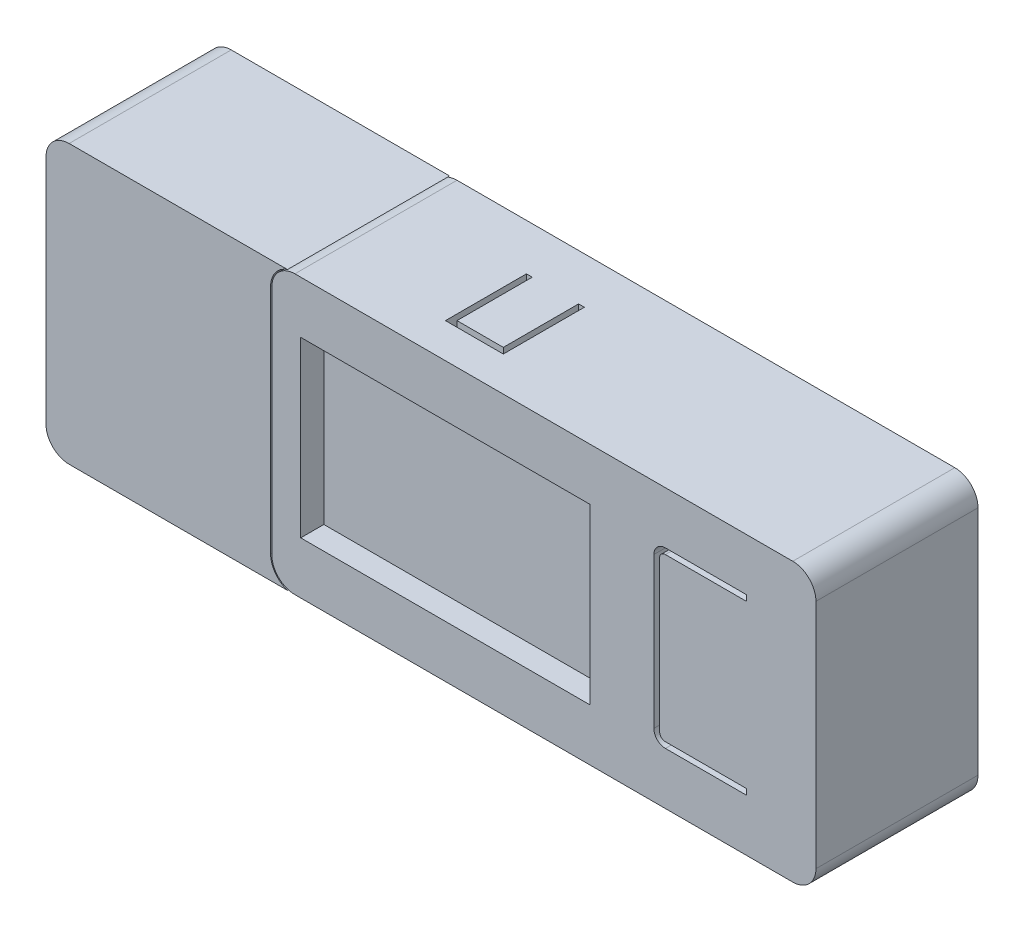
SolidWorks part; units mm, degrees
ref_plane "Alzado" through (0, 0, 0) normal (0, 0, 1) x (1, 0, 0)
ref_plane "Planta" through (0, 0, 0) normal (0, 1, 0) x (1, 0, 0)
ref_plane "Vista lateral" through (0, 0, 0) normal (1, 0, 0) x (0, 0, -1)
sketch "Croquis1" plane through (0, 0, 0) normal (0, 0, 1) x (1, 0, 0)
  line L1 (23.5, 12) -> (-23.5, 12)
  line L2 (23.5, 12) -> (23.5, -12)
  line L3 (23.5, -12) -> (-23.5, -12)
  line L4 (-23.5, 12) -> (-23.5, -12)
  line L5 (23.5, 12) -> (-23.5, -12) construction
  line L6 (23.5, -12) -> (-23.5, 12) construction
  point P0 (0, 0)
  dimension "D1" = 47
  dimension "D2" = 24
extrude "Saliente-Extruir1" add sketch "Croquis1" along normal blind 14
fillet "Redondeo1" radius 2 4 edges at (-23.5, -12, 7) (-23.5, 12, 7) (23.5, -12, 7) (23.5, 12, 7)
sketch "Croquis2" plane through (0, 0, 14) normal (0, 0, 1) x (1, 0, 0)
  line L0 (23.5, -10) -> (23.5, 10) construction
  line L1 (4, 7.5) -> (-21, 7.5)
  line L2 (4, 7.5) -> (4, -7.5)
  line L3 (4, -7.5) -> (-21, -7.5)
  line L4 (-21, 7.5) -> (-21, -7.5)
  line L5 (4, 7.5) -> (-21, -7.5) construction
  line L6 (4, -7.5) -> (-21, 7.5) construction
  line L7 (17.5, 7.5) -> (10.5, 7.5)
  line L8 (9.5, 6.5) -> (9.5, -6.5)
  line L9 (10.5, -7.5) -> (17.5, -7.5)
  line L10 (17.5, 7) -> (10.5, 7)
  line L11 (10, 6.5) -> (10, -6.5)
  line L12 (10.5, -7) -> (17.5, -7)
  line L13 (17.5, 7.5) -> (17.5, 7)
  line L14 (17.5, -7) -> (17.5, -7.5)
  arc A0 (10.5, 7.5) -> (9.5, 6.5) centre (10.5, 6.5) ccw
  arc A1 (9.5, -6.5) -> (10.5, -7.5) centre (10.5, -6.5) ccw
  arc A2 (10.5, 7) -> (10, 6.5) centre (10.5, 6.5) ccw
  arc A3 (10, -6.5) -> (10.5, -7) centre (10.5, -6.5) ccw
  point P0 (-8.5, 0)
  point P5 (9.5, 0)
  dimension "D6" = 1
  dimension "D1" = 25
  dimension "D2" = 19.5
  dimension "D3" = 15
  dimension "D4" = 8
  dimension "D5" = 6
  dimension "D7" = 0.5
extrude "Cortar-Extruir1" cut sketch "Croquis2" against normal blind 2
sketch "Croquis3" plane through (0, 12, 0) normal (0, 1, 0) x (1, 0, 0)
  line L0 (-6.5, -4) -> (-6.5, -11)
  line L1 (-6.5, -11) -> (-11.5, -11)
  line L2 (-11.5, -11) -> (-11.5, -4)
  line L3 (23.5, 0) -> (23.5, -14) construction
  line L4 (21.5, -14) -> (-21.5, -14) construction
  line L5 (21.5, 0) -> (-21.5, 0) construction
  line L6 (-7, -4) -> (-7, -10.5)
  line L7 (-7, -10.5) -> (-11, -10.5)
  line L8 (-11, -10.5) -> (-11, -4)
  line L9 (-11.5, -4) -> (-11, -4)
  line L10 (-7, -4) -> (-6.5, -4)
  dimension "D1" = 30
  dimension "D2" = 5
  dimension "D3" = 3
  dimension "D4" = 4
  dimension "D5" = 0.5
extrude "Cortar-Extruir2" cut sketch "Croquis3" against normal blind 5
sketch "Croquis4" plane through (0, -12, 0) normal (0, -1, 0) x (1, 0, 0)
  line L0 (16.5, 11) -> (16.5, 4)
  line L1 (16.5, 4) -> (11.5, 4)
  line L2 (11.5, 4) -> (11.5, 11)
  line L3 (23.5, 14) -> (23.5, 0) construction
  line L4 (-21.5, 14) -> (21.5, 14) construction
  line L5 (-21.5, 0) -> (21.5, 0) construction
  line L6 (16, 11) -> (16, 4.5)
  line L7 (16, 4.5) -> (12, 4.5)
  line L8 (12, 4.5) -> (12, 11)
  line L9 (11.5, 11) -> (12, 11)
  line L10 (16, 11) -> (16.5, 11)
  dimension "D1" = 5
  dimension "D2" = 7
  dimension "D3" = 3
  dimension "D4" = 4
  dimension "D5" = 0.5
extrude "Cortar-Extruir3" cut sketch "Croquis4" against normal blind 5
sketch "Croquis5" plane through (0, 0, 0) normal (0, 0, 1) x (1, 0, 0)
  line L0 (-22.1403, 12) -> (-41, 12)
  line L1 (-43, 10) -> (-43, -10)
  line L2 (-41, -12) -> (-22.1403, -12)
  line L3 (23.5, -10) -> (23.5, 10) construction
  line L9 (-23.6, 10) -> (-23.6, -10)
  line L10 (-23.6, 10) -> (-23.6, -10)
  arc A0 (-43, -10) -> (-41, -12) centre (-41, -10) ccw
  arc A1 (-41, 12) -> (-43, 10) centre (-41, 10) ccw
  arc A10 (-23.6, -10) -> (-21.5, -12.1) centre (-21.5, -10) ccw
  arc A11 (-21.5, 12.1) -> (-23.6, 10) centre (-21.5, 10) ccw
  arc A12 (-23.6, -10) -> (-22.1403, -12) centre (-21.5, -10) ccw
  arc A13 (-22.1403, 12) -> (-23.6, 10) centre (-21.5, 10) ccw
  dimension "D2" = 2
  dimension "D3" = 0.1
  dimension "D1" = 66.5
  dimension "D4" = 0.6403
  dimension "D5" = 0.6403
extrude "Saliente-Extruir3" add sketch "Croquis5" along normal up to surface (14 mm away) separate body up to face at (-8.5, 0, 14)
sketch "Croquis6" plane through (0, 0, 0) normal (0, 0, -1) x (-1, 0, 0)
  line L0 (-14, 8) -> (-14, -8) construction
  line L1 (43, 10) -> (43, -10) construction
  circle A0 centre (36, 0) radius 4.5
  circle A1 centre (-14, 8) radius 1
  circle A2 centre (-14, -8) radius 1
  point P6 (-14, 0)
  dimension "D1" = 2
  dimension "D4" = 9
  dimension "D5" = 7
  dimension "D2" = 57
  dimension "D3" = 16
extrude "Cortar-Extruir4" cut sketch "Croquis6" against normal blind 2
sketch "Croquis7" plane through (0, 0, 0) normal (0, 0, -1) x (-1, 0, 0)
  point P0 (36, 0)
  point P1 (36, 0)
